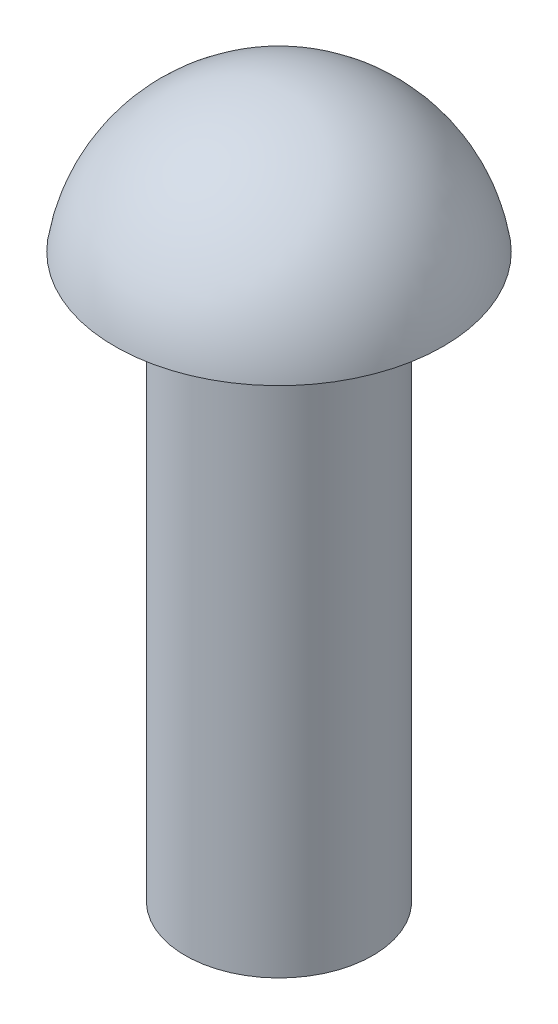
SolidWorks part; units mm, degrees
material "2.0060 (Cu-ETP)"
ref_plane "Front Plane" through (0, 0, 0) normal (0, 0, 1) x (1, 0, 0)
ref_plane "Top Plane" through (0, 0, 0) normal (0, 1, 0) x (1, 0, 0)
ref_plane "Right Plane" through (0, 0, 0) normal (1, 0, 0) x (0, 0, -1)
sketch "Sketch1" plane through (0, 0, 0) normal (0, 0, 1) x (1, 0, 0)
  line L0 (0, 0) -> (6.35, 0)
  line L1 (6.35, 0) -> (6.35, 38.1)
  line L2 (6.35, 38.1) -> (11.1188, 38.1)
  line L3 (0, 0) -> (0, 47.625)
  arc A1 (11.1188, 38.1) -> (0, 47.625) centre (0, 36.3728) ccw
  point P8 (0, 64.8536)
  dimension "D1" = 11.2522
  dimension "D2" = 6.35
  dimension "D3" = 38.1
  dimension "D4" = 9.525
revolve "Revolve1" add sketch "Sketch1" angle 360 about L3
